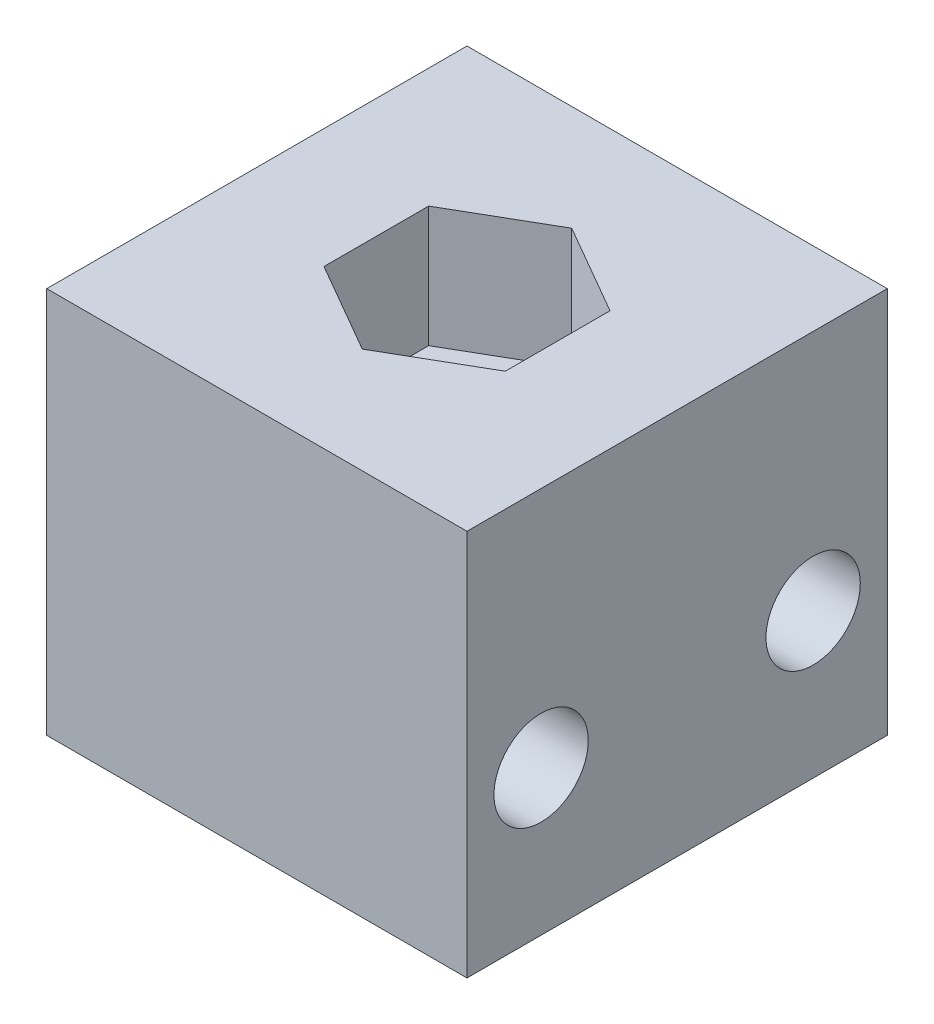
SolidWorks part; units mm, degrees
material "ABS"
ref_plane "Front Plane" through (0, 0, 0) normal (0, 0, 1) x (1, 0, 0)
ref_plane "Top Plane" through (0, 0, 0) normal (0, 1, 0) x (1, 0, 0)
ref_plane "Right Plane" through (0, 0, 0) normal (1, 0, 0) x (0, 0, -1)
sketch "Sketch1" plane through (0, 0, 0) normal (0, 1, 0) x (1, 0, 0)
  line L1 (-11.0363, -11.0363) -> (11.0363, -11.0363)
  line L2 (-11.0363, -11.0363) -> (-11.0363, 11.0363)
  line L3 (-11.0363, 11.0363) -> (11.0363, 11.0363)
  line L4 (11.0363, -11.0363) -> (11.0363, 11.0363)
  line L5 (-11.0363, -11.0363) -> (11.0363, 11.0363) construction
  line L6 (-11.0363, 11.0363) -> (11.0363, -11.0363) construction
  point P0 (0, 0)
  dimension "D1" = 22.0726
extrude "Boss-Extrude1" add sketch "Sketch1" along normal blind 20.32
sketch "Sketch5" plane through (0, 0, 0) normal (0, -1, 0) x (1, 0, 0)
  point P0 (0, 0)
hole_wizard "#10 Clearance Hole1" positions "Sketch6" profile "Sketch7" hole size "#10" standard "ANSI Inch" end condition through all
sketch "Sketch6" plane through (0, 0, 0) normal (0, -1, 0) x (-1, 0, 0)
  point P0 (0, 0)
sketch "Sketch7" plane through (0, 0, 0) normal (1, 0, 0) x (0, 0, -1)
  line L0 (0, 0) -> (0, 20.32)
  line L1 (0, 20.32) -> (2.4892, 20.32)
  line L2 (2.4892, 20.32) -> (2.4892, 0)
  line L5 (2.4892, 0) -> (0, 0)
  line L11 (0, -6.35) -> (0, 107.95) construction
  dimension "Thru Hole Dia." = 4.9784
  dimension "Thru Hole Depth" = 20.32
sketch "Sketch8" plane through (11.0363, 0, 0) normal (1, 0, 0) x (0, 0, -1)
  line L0 (-7.1438, 7.62) -> (0, 7.62) construction
  line L1 (-11.0363, 0) -> (11.0363, 0) construction
  line L4 (0, 20.32) -> (0, 0) construction
  line L5 (-11.0363, 20.32) -> (11.0363, 20.32) construction
  line L6 (0, 7.62) -> (7.1437, 7.62) construction
  circle A0 centre (-7.1438, 7.62) radius 2.4765
  circle A1 centre (7.1437, 7.62) radius 2.4765
  point P6 (-7.1438, 7.62)
  point P7 (7.1437, 7.62)
  dimension "D3" = 4.953
  dimension "D1" = 7.62
  dimension "D2" = 14.2875
extrude "Cut-Extrude1" cut sketch "Sketch8" against normal through all
sketch "Sketch9" plane through (0, 20.32, 0) normal (0, 1, 0) x (1, 0, 0)
  line L1 (0, 5.4993) -> (-4.7625, 2.7496)
  line L2 (-4.7625, 2.7496) -> (-4.7625, -2.7496)
  line L3 (-4.7625, -2.7496) -> (0, -5.4993)
  line L4 (0, -5.4993) -> (4.7625, -2.7496)
  line L5 (4.7625, -2.7496) -> (4.7625, 2.7496)
  line L6 (4.7625, 2.7496) -> (0, 5.4993)
  circle A0 centre (0, 0) radius 4.7625 construction
  dimension "D1" = 9.525
extrude "Cut-Extrude2" cut sketch "Sketch9" against normal blind 6.35
